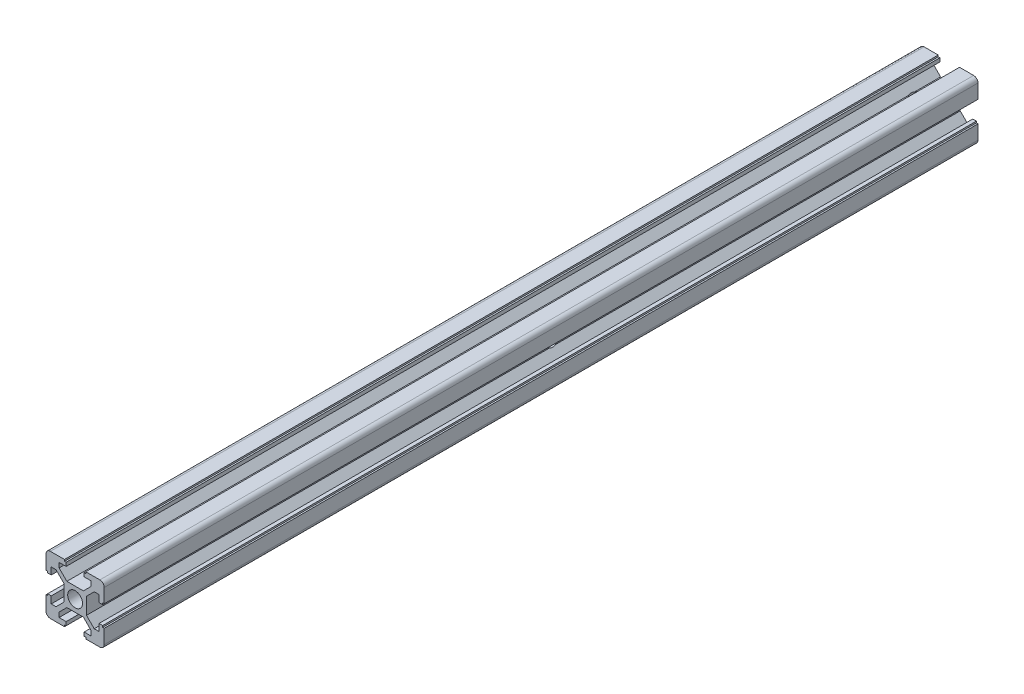
SolidWorks part; units mm, degrees
material "6063-T5"
ref_plane "前视基准面" through (0, 0, 0) normal (0, 0, 1) x (1, 0, 0)
ref_plane "上视基准面" through (0, 0, 0) normal (0, 1, 0) x (1, 0, 0)
ref_plane "右视基准面" through (0, 0, 0) normal (1, 0, 0) x (0, 0, -1)
sketch "草图1" plane through (0, 0, 0) normal (0, 0, 1) x (1, 0, 0)
  line L0 (-3.9, 2.8393) -> (-6.5607, 5.5)
  line L1 (-2.8393, 3.9) -> (2.8393, 3.9)
  line L2 (-3.9, 2.8393) -> (-3.9, -2.8393)
  line L3 (-2.8393, -3.9) -> (2.8393, -3.9)
  line L4 (3.9, 2.8393) -> (3.9, -2.8393)
  line L5 (-3.9, 3.9) -> (3.9, -3.9) construction
  line L6 (-3.9, -3.9) -> (3.9, 3.9) construction
  line L7 (-2.8393, 3.9) -> (-5.5, 6.5607)
  line L8 (-5.5, 6.5607) -> (-5.5, 8.2)
  line L9 (-5.5, 8.2) -> (-3.1, 8.2)
  line L10 (-3.1, 8.2) -> (-3.1, 9.45)
  line L11 (-3.1, 9.45) -> (-3.65, 9.45)
  line L12 (-3.65, 9.45) -> (-3.65, 10)
  line L13 (-3.65, 10) -> (-8.5, 10)
  line L14 (-6.5607, 5.5) -> (-8.2, 5.5)
  line L15 (-10, 3.65) -> (-10, 8.5)
  line L16 (-9.45, 3.65) -> (-10, 3.65)
  line L17 (-9.45, 3.1) -> (-9.45, 3.65)
  line L18 (-8.2, 3.1) -> (-9.45, 3.1)
  line L19 (-8.2, 5.5) -> (-8.2, 3.1)
  line L20 (2.8393, 3.9) -> (5.5, 6.5607)
  line L21 (3.9, 2.8393) -> (6.5607, 5.5)
  line L22 (6.5607, 5.5) -> (8.2, 5.5)
  line L23 (8.2, 5.5) -> (8.2, 3.1)
  line L24 (8.2, 3.1) -> (9.45, 3.1)
  line L25 (9.45, 3.1) -> (9.45, 3.65)
  line L26 (9.45, 3.65) -> (10, 3.65)
  line L27 (10, 3.65) -> (10, 8.5)
  line L28 (5.5, 6.5607) -> (5.5, 8.2)
  line L29 (3.65, 10) -> (8.5, 10)
  line L30 (3.65, 9.45) -> (3.65, 10)
  line L31 (3.1, 9.45) -> (3.65, 9.45)
  line L32 (3.1, 8.2) -> (3.1, 9.45)
  line L33 (5.5, 8.2) -> (3.1, 8.2)
  line L34 (3.9, -2.8393) -> (6.5607, -5.5)
  line L35 (2.8393, -3.9) -> (5.5, -6.5607)
  line L36 (5.5, -6.5607) -> (5.5, -8.2)
  line L37 (5.5, -8.2) -> (3.1, -8.2)
  line L38 (3.1, -8.2) -> (3.1, -9.45)
  line L39 (3.1, -9.45) -> (3.65, -9.45)
  line L40 (3.65, -9.45) -> (3.65, -10)
  line L41 (3.65, -10) -> (8.5, -10)
  line L42 (6.5607, -5.5) -> (8.2, -5.5)
  line L43 (10, -3.65) -> (10, -8.5)
  line L44 (9.45, -3.65) -> (10, -3.65)
  line L45 (9.45, -3.1) -> (9.45, -3.65)
  line L46 (8.2, -3.1) -> (9.45, -3.1)
  line L47 (8.2, -5.5) -> (8.2, -3.1)
  line L48 (-2.8393, -3.9) -> (-5.5, -6.5607)
  line L49 (-3.9, -2.8393) -> (-6.5607, -5.5)
  line L50 (-6.5607, -5.5) -> (-8.2, -5.5)
  line L51 (-8.2, -5.5) -> (-8.2, -3.1)
  line L52 (-8.2, -3.1) -> (-9.45, -3.1)
  line L53 (-9.45, -3.1) -> (-9.45, -3.65)
  line L54 (-9.45, -3.65) -> (-10, -3.65)
  line L55 (-10, -3.65) -> (-10, -8.5)
  line L56 (-5.5, -6.5607) -> (-5.5, -8.2)
  line L57 (-3.65, -10) -> (-8.5, -10)
  line L58 (-3.65, -9.45) -> (-3.65, -10)
  line L59 (-3.1, -9.45) -> (-3.65, -9.45)
  line L60 (-3.1, -8.2) -> (-3.1, -9.45)
  line L61 (-5.5, -8.2) -> (-3.1, -8.2)
  circle A0 centre (0, 0) radius 2.55
  arc A1 (-8.5, 10) -> (-10, 8.5) centre (-8.5, 8.5) ccw
  arc A2 (10, 8.5) -> (8.5, 10) centre (8.5, 8.5) ccw
  arc A3 (8.5, -10) -> (10, -8.5) centre (8.5, -8.5) ccw
  arc A4 (-10, -8.5) -> (-8.5, -10) centre (-8.5, -8.5) ccw
  point P74 (0, 0)
  dimension "D1" = 5.1
  dimension "D8" = 1.5
  dimension "D2" = 7.8
  dimension "D3" = 1.5
  dimension "D4" = 3.1
  dimension "D5" = 0.55
  dimension "D6" = 1.8
  dimension "D7" = 5.5
  dimension "D9" = 3.9
extrude "凸台-拉伸1" add sketch "草图1" along normal blind 300
sketch "草图2" plane through (0, 10, 0) normal (0, 1, 0) x (1, 0, 0)
  line L0 (2.8393, 0) -> (-2.8393, 0) construction
  line L1 (0, -10) -> (0, 0) construction
  circle A0 centre (0, -10) radius 3
  dimension "D1" = 6
  dimension "D2" = 10
extrude "切除-拉伸1" cut sketch "草图2" against normal through all
sketch "草图3" plane through (10, 0, 0) normal (1, 0, 0) x (0, 0, -1)
  line L0 (-300, 0) -> (-140, 0) construction
  line L1 (-300, -2.8393) -> (-300, 2.8393) construction
  circle A0 centre (-140, 0) radius 3
  dimension "D1" = 6
  dimension "D2" = 160
extrude "切除-拉伸2" cut sketch "草图3" against normal through all
